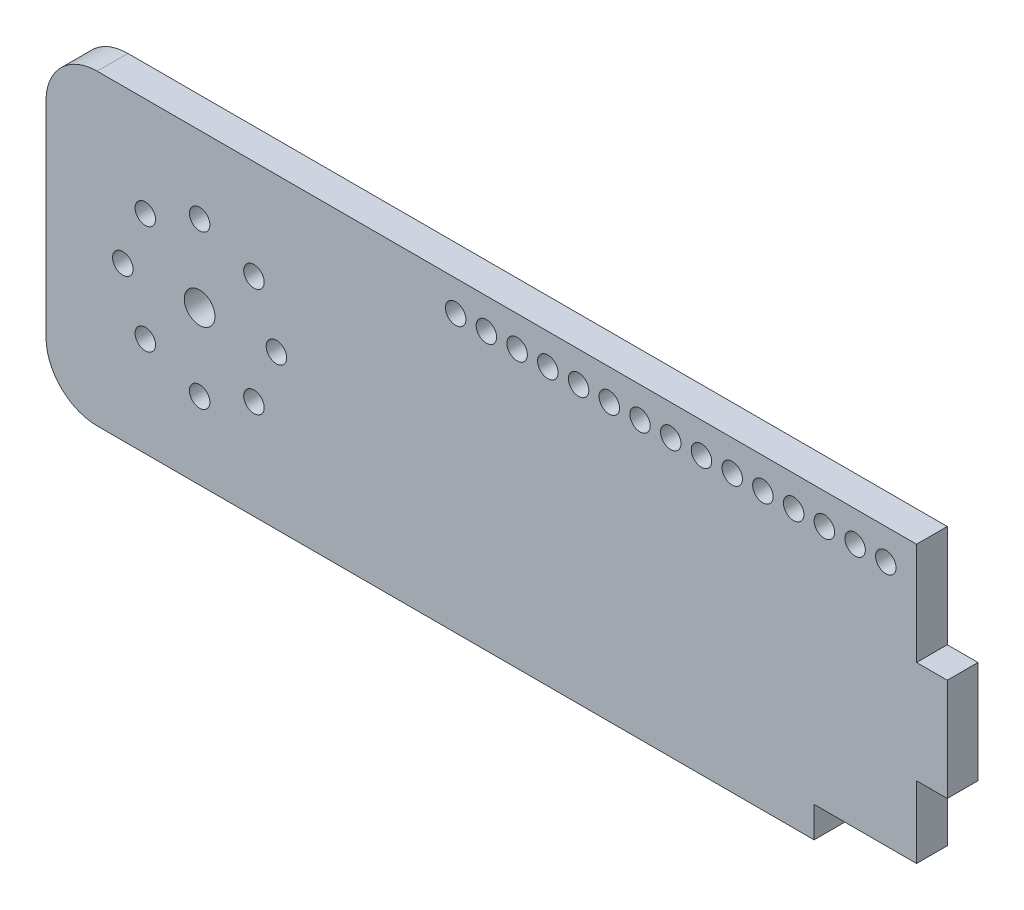
SolidWorks part; units mm, degrees
ref_plane "Front Plane" through (0, 0, 0) normal (0, 0, 1) x (1, 0, 0)
ref_plane "Top Plane" through (0, 0, 0) normal (0, 1, 0) x (1, 0, 0)
ref_plane "Right Plane" through (0, 0, 0) normal (1, 0, 0) x (0, 0, -1)
sketch "Sketch1" plane through (0, 0, 0) normal (0, 0, 1) x (1, 0, 0)
  line L0 (85, 30) -> (85, 20)
  line L1 (0, 0) -> (75, 0)
  line L2 (0, 0) -> (0, 30)
  line L3 (0, 30) -> (85, 30)
  line L4 (85, 3) -> (85, 10)
  line L5 (85, 20) -> (88, 20)
  line L6 (88, 20) -> (88, 10)
  line L7 (88, 10) -> (85, 10)
  line L8 (85, 20) -> (85, 30)
  line L9 (0, 15) -> (15, 15)
  line L13 (85, 3) -> (75, 3)
  line L14 (75, 0) -> (75, 3)
  circle A0 centre (15, 15) radius 1.5
  circle A1 centre (7.5, 15) radius 1
  circle A2 centre (9.6967, 20.3033) radius 1
  circle A3 centre (15, 22.5) radius 1
  circle A4 centre (20.3033, 20.3033) radius 1
  circle A5 centre (22.5, 15) radius 1
  circle A6 centre (20.3033, 9.6967) radius 1
  circle A7 centre (15, 7.5) radius 1
  circle A8 centre (9.6967, 9.6967) radius 1
  circle A9 centre (82, 27) radius 1
  circle A10 centre (79, 27) radius 1
  circle A11 centre (76, 27) radius 1
  circle A12 centre (73, 27) radius 1
  circle A13 centre (70, 27) radius 1
  circle A14 centre (67, 27) radius 1
  circle A15 centre (64, 27) radius 1
  circle A16 centre (61, 27) radius 1
  circle A17 centre (58, 27) radius 1
  circle A18 centre (55, 27) radius 1
  circle A19 centre (52, 27) radius 1
  circle A20 centre (49, 27) radius 1
  circle A21 centre (46, 27) radius 1
  circle A22 centre (43, 27) radius 1
  circle A23 centre (40, 27) radius 1
  point P31 (15, 15)
  dimension "D7" = 3
  dimension "D8" = 2
  dimension "D10" = 2
  dimension "D1" = 85
  dimension "D2" = 30
  dimension "D3" = 10
  dimension "D4" = 10
  dimension "D5" = 3
  dimension "D6" = 15
  dimension "D11" = 3
  dimension "D12" = 3
  dimension "D14" = 3
  dimension "D15" = 10
  dimension "D13" = 15
  dimension "D9" = 8
extrude "Boss-Extrude1" add sketch "Sketch1" along normal blind 3
fillet "Fillet1" radius 5 2 edges at (0, 0, 1.5) (0, 30, 1.5)
